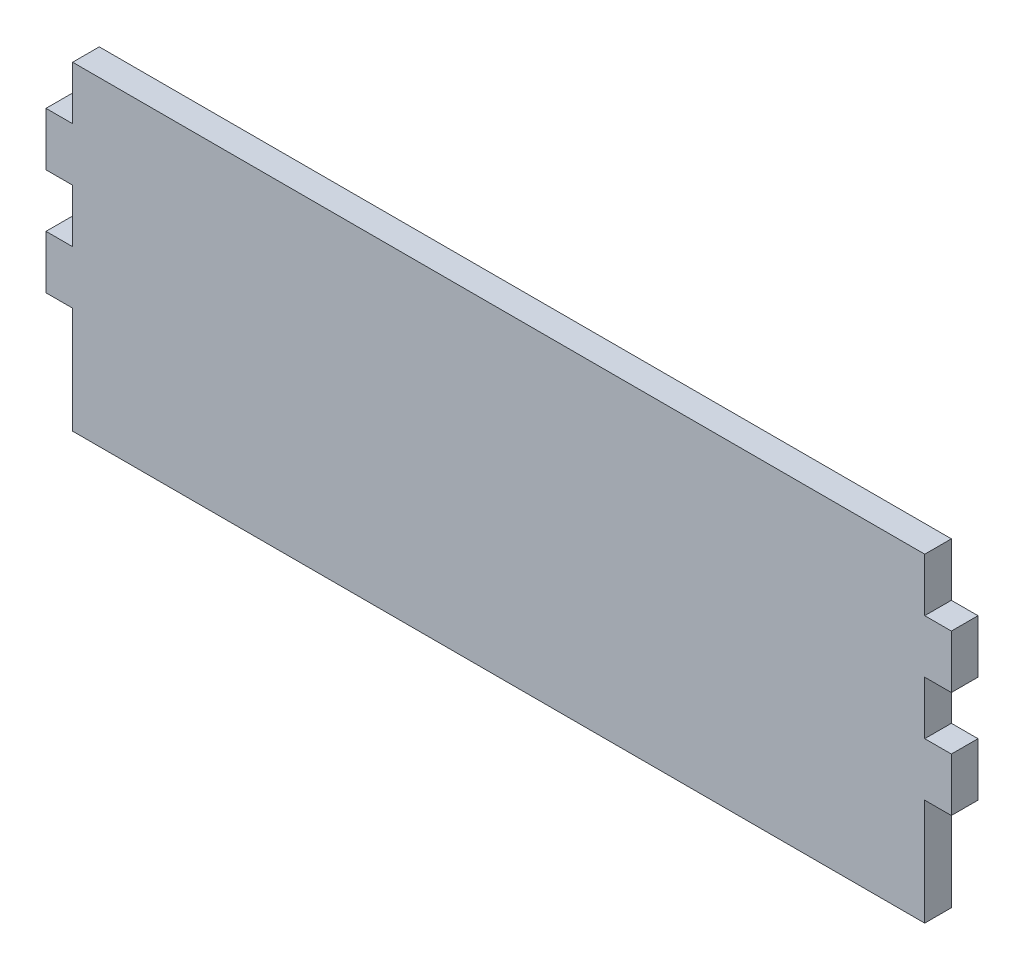
SolidWorks part; units mm, degrees
ref_plane "Front Plane" through (0, 0, 0) normal (0, 0, 1) x (1, 0, 0)
ref_plane "Top Plane" through (0, 0, 0) normal (0, 1, 0) x (1, 0, 0)
ref_plane "Right Plane" through (0, 0, 0) normal (1, 0, 0) x (0, 0, -1)
sketch "Sketch1" plane through (0, 0, 0) normal (0, 0, 1) x (1, 0, 0)
  line L0 (0, 0) -> (0, 31.4953) construction
  line L1 (-42.5, 15) -> (-42.5, 10)
  line L2 (-40, 0) -> (40, 0)
  line L3 (-40, 10) -> (-42.5, 10)
  line L4 (-40, 30) -> (40, 30)
  line L5 (40, 0) -> (40, 10)
  line L6 (40, 25) -> (42.5, 25)
  line L7 (40, 25) -> (40, 30)
  line L8 (40, 20) -> (42.5, 20)
  line L9 (42.5, 25) -> (42.5, 20)
  line L10 (40, 15) -> (42.5, 15)
  line L11 (-40, 15) -> (-40, 20)
  line L12 (40, 10) -> (42.5, 10)
  line L13 (42.5, 15) -> (42.5, 10)
  line L14 (-40, 25) -> (-40, 30)
  line L15 (-40, 15) -> (-42.5, 15)
  line L16 (-42.5, 25) -> (-42.5, 20)
  line L17 (-40, 20) -> (-42.5, 20)
  line L19 (-40, 25) -> (-42.5, 25)
  line L20 (-40, 0) -> (-40, 10)
  line L21 (40, 15) -> (40, 20)
  point P14 (41.25, 25)
  point P26 (0, 30)
  dimension "D1" = 40
  dimension "D2" = 30
  dimension "D3" = 5
  dimension "D4" = 2.5
  dimension "D5" = 5
  dimension "D6" = 5
extrude "Boss-Extrude1" add sketch "Sketch1" along normal blind 2.5
equation "\"t\"=2.5"
equation "\"D4@Sketch1\"=\"t\""
equation "\"D1@Boss-Extrude1\"=\"t\""
